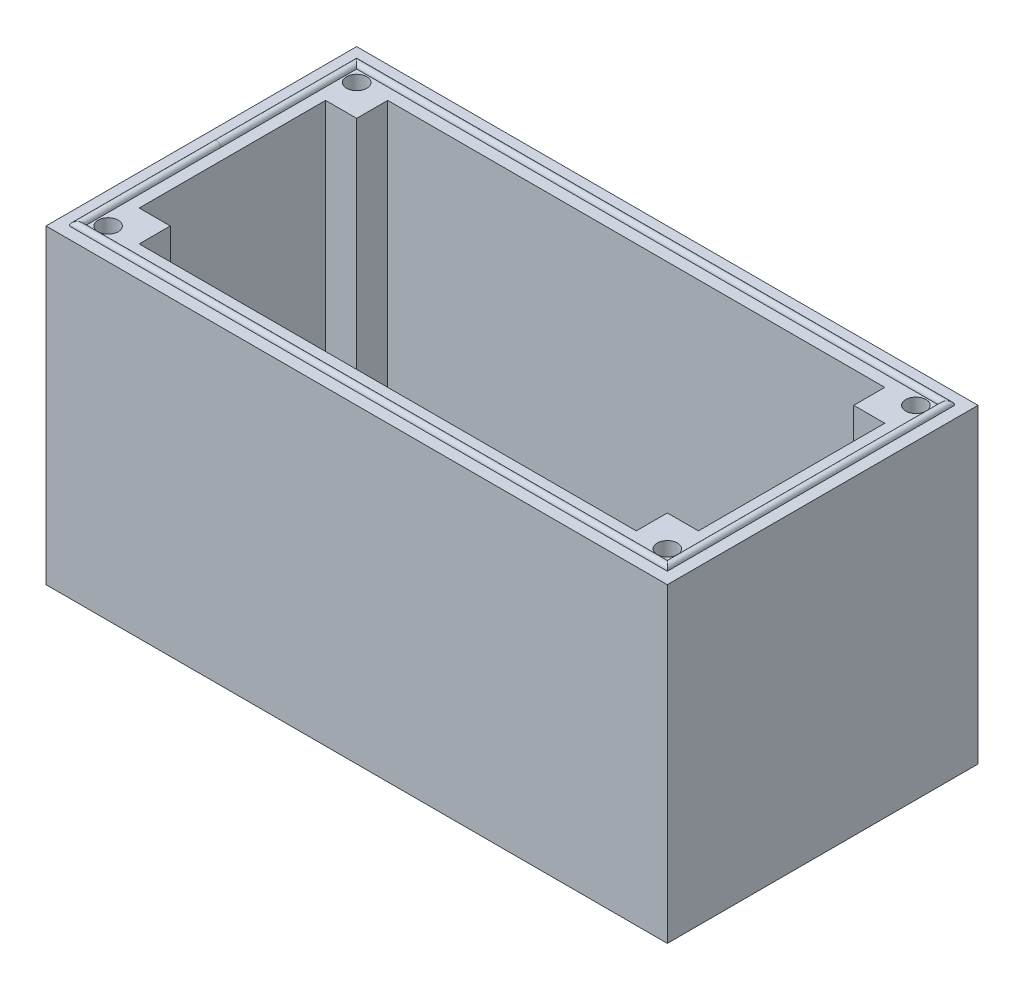
SolidWorks part; units mm, degrees
ref_plane "Piano frontale" through (0, 0, 0) normal (0, 0, 1) x (1, 0, 0)
ref_plane "Piano superiore" through (0, 0, 0) normal (0, 1, 0) x (1, 0, 0)
ref_plane "Piano destro" through (0, 0, 0) normal (1, 0, 0) x (0, 0, -1)
sketch "Schizzo1" plane through (0, 0, 0) normal (0, 0, 1) x (1, 0, 0)
  line L0 (0, 0) -> (0, 20)
  line L1 (0, 20) -> (40, 20)
  line L2 (40, 20) -> (40, 0)
  line L3 (40, 0) -> (0, 0)
  dimension "D1" = 40
  dimension "D2" = 20
extrude "Estrusione-Estrusione1" add sketch "Schizzo1" against normal blind 20
sketch "Schizzo2" plane through (0, 20, 0) normal (0, 1, 0) x (1, 0, 0)
  line L0 (0, 10) -> (40, 10) construction
  line L1 (0, 20) -> (0, 0) construction
  line L2 (40, 20) -> (40, 0) construction
  line L3 (20, 20) -> (20, 0) construction
  line L4 (40, 20) -> (0, 20) construction
  line L5 (40, 0) -> (0, 0) construction
  line L6 (4, 18) -> (4, 16)
  line L7 (36, 2) -> (4, 2)
  line L8 (38, 4) -> (38, 16)
  line L9 (36, 18) -> (4, 18)
  line L10 (2, 4) -> (2, 16)
  line L11 (36, 2.8889) -> (4, 17.1111) construction
  line L12 (36, 17.1111) -> (4, 2.8889) construction
  line L13 (4, 16) -> (2, 16)
  line L14 (2, 4) -> (4, 4)
  line L15 (4, 4) -> (4, 2)
  line L16 (36, 18) -> (36, 16)
  line L17 (36, 16) -> (38, 16)
  line L18 (38, 4) -> (36, 4)
  line L19 (36, 4) -> (36, 2)
  point P12 (20, 10)
  dimension "D1" = 2
  dimension "D2" = 2
  dimension "D3" = 2
extrude "Taglio-Estrusione1" cut sketch "Schizzo2" against normal blind 20 contours L8 L17 L16 L9 L6 L13 L10 L14 L15 L7 L19 L18
ref_plane "Piano1" through (0, 0, -10) normal (0, 0, 1) x (1, 0, 0)
sketch "Schizzo3" plane through (0, 0, -10) normal (0, 0, 1) x (1, 0, 0)
  line L0 (40, 20) -> (0, 20) construction
  line L1 (0.75, 20) -> (1.25, 20)
  arc A0 (1.25, 20) -> (0.75, 20) centre (1, 20) ccw
  point P0 (1.999, 20)
  dimension "D1" = 0.5
  dimension "D2" = 1
sketch "Schizzo4" plane through (0, 20, 0) normal (0, 1, 0) x (1, 0, 0)
  line L0 (0, 10) -> (40, 10) construction
  line L1 (0, 20) -> (0, 0) construction
  line L2 (-11.1375, 10) -> (11.1375, 10) construction
  line L3 (20, 0) -> (20, 20) construction
  line L4 (40, 0) -> (0, 0) construction
  line L5 (40, 20) -> (0, 20) construction
  line L6 (40, 20) -> (40, 0) construction
  line L7 (1, 19) -> (39, 19)
  line L8 (1, 19) -> (1, 1)
  line L9 (1, 1) -> (39, 1)
  line L10 (39, 19) -> (39, 1)
  line L11 (1, 19) -> (39, 1) construction
  line L12 (1, 1) -> (39, 19) construction
  point P12 (20, 10)
  dimension "D1" = 1
  dimension "D2" = 1
  dimension "D3" = 1
sweep "Sweep1" add profiles "Schizzo3" path "Schizzo4"
sketch "Schizzo5" plane through (0, 0, 0) normal (0, -1, 0) x (1, 0, 0)
  line L4 (1, -19) -> (39, -19)
  line L5 (1, -1) -> (1, -19)
  line L6 (39, -1) -> (1, -1)
  line L7 (39, -19) -> (39, -1)
  line L8 (1, -19) -> (39, -19)
  line L9 (1, -1) -> (1, -19)
  line L10 (39, -1) -> (1, -1)
  line L11 (39, -19) -> (39, -1)
  dimension "D1" = 0
sketch "Schizzo6" plane through (0, 0, -10) normal (0, 0, 1) x (1, 0, 0)
  line L0 (39, 0) -> (1, 0) construction
  line L1 (1, 0) -> (39, 0) construction
  line L2 (0, 20) -> (0, 0) construction
  line L3 (0.75, 0) -> (1.25, 0)
  arc A0 (1.25, 0) -> (0.75, 0) centre (1, 0) ccw
  dimension "D1" = 0.5
  dimension "D2" = 1
sweep "Taglia-Sweep1" cut profiles "Schizzo6" path "Schizzo5"
hole_wizard "Foro per Vite M1-1" positions "Schizzo7" profile "Schizzo9" hole size "M1" standard "KS" end condition through all
sketch "Schizzo7" plane through (0, 0, 0) normal (0, -1, 0) x (-1, 0, 0)
  line L0 (-40, 20) -> (-40, 0) construction
  line L1 (0, 20) -> (-40, 20) construction
  point P0 (-38, 18)
  dimension "D1" = 2
  dimension "D2" = 2
sketch "Schizzo9" plane through (38, 0, -18) normal (1, 0, 0) x (0, 0, -1)
  line L0 (0, 0) -> (0, 20.25)
  line L1 (0, 20.25) -> (0.65, 20.25)
  line L2 (0.65, 20.25) -> (0.65, 0.025)
  line L3 (0.65, 0.025) -> (0.675, 0)
  line L5 (0.675, 0) -> (0, 0)
  line L6 (-0.65, 0.025) -> (-0.675, 0) construction
  line L11 (0, -6.35) -> (0, 107.95) construction
  dimension "Thru Hole Dia." = 1.3
  dimension "Thru Hole Depth" = 20.25
  dimension "Near C'Sink Dia." = 1.35
  dimension "Near C'Sink Angle" = 90
mirror "Specchia1" about plane through (0, 0, -10) normal (0, 0, 1) of "Foro per Vite M1-1"
ref_plane "Piano2" through (20, 0, 0) normal (1, 0, 0) x (0, 0, -1)
mirror "Specchia2" about plane through (20, 0, 0) normal (1, 0, 0) of "Specchia1", "Foro per Vite M1-1"
